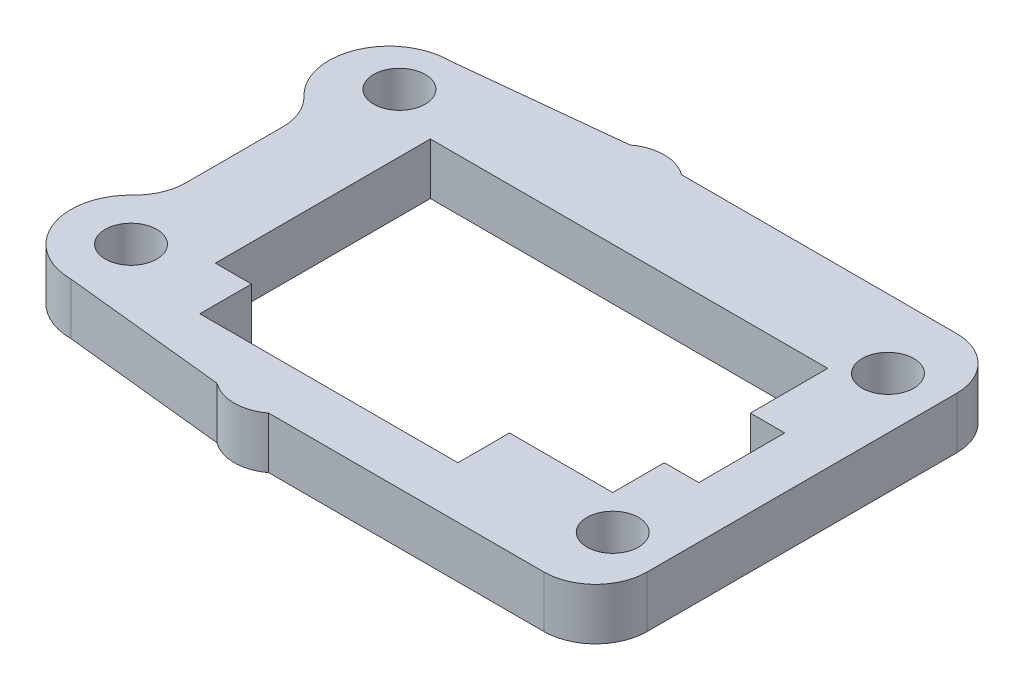
SolidWorks part; units mm, degrees
ref_plane "Alzado" through (0, 0, 0) normal (0, 0, 1) x (1, 0, 0)
ref_plane "Planta" through (0, 0, 0) normal (0, 1, 0) x (1, 0, 0)
ref_plane "Vista lateral" through (0, 0, 0) normal (1, 0, 0) x (0, 0, -1)
sketch "Croquis1" plane through (0, 0, 0) normal (0, 0, 1) x (1, 0, 0)
  line L0 (41558.3613, 58239.9576) -> (41574.3613, 58239.9576)
  line L1 (41544.3613, 58230.7672) -> (41544.3613, 58225.148)
  line L2 (41545.8613, 58216.9576) -> (41555.3613, 58215.9576)
  line L3 (41558.3613, 58215.9576) -> (41574.3613, 58215.9576)
  line L4 (41577.3613, 58218.9576) -> (41577.3613, 58236.9576)
  line L5 (41555.3613, 58239.9576) -> (41545.8613, 58238.9576)
  line L6 (41551.3613, 58236.9576) -> (41566.3613, 58236.9576)
  line L7 (41566.3613, 58236.9576) -> (41566.3613, 58233.9576)
  line L8 (41566.3613, 58233.9576) -> (41572.3613, 58233.9576)
  line L9 (41572.3613, 58233.9576) -> (41572.3613, 58230.9576)
  line L10 (41572.3613, 58230.9576) -> (41574.3613, 58230.9576)
  line L11 (41574.3613, 58230.9576) -> (41574.3613, 58225.9576)
  line L12 (41574.3613, 58225.9576) -> (41572.3613, 58225.9576)
  line L13 (41572.3613, 58225.9576) -> (41572.3613, 58221.4576)
  line L14 (41572.3613, 58221.4576) -> (41549.2613, 58221.4576)
  line L15 (41549.2613, 58221.4576) -> (41549.2613, 58233.9576)
  line L16 (41549.2613, 58233.9576) -> (41551.3613, 58233.9576)
  line L17 (41551.3613, 58233.9576) -> (41551.3613, 58236.9576)
  circle A0 centre (41545.8613, 58235.4576) radius 1.5
  arc A1 (41545.8613, 58238.9576) -> (41543.4382, 58232.932) centre (41545.8613, 58235.4576) ccw
  circle A4 centre (41545.8613, 58219.8576) radius 1.5
  arc A5 (41543.4382, 58222.9832) -> (41545.8613, 58216.9576) centre (41545.8613, 58220.4576) ccw
  arc A6 (41555.3613, 58215.9576) -> (41558.3613, 58215.9576) centre (41556.8613, 58217.9576) ccw
  circle A7 centre (41574.3613, 58219.9576) radius 1.5
  circle A8 centre (41574.3613, 58235.9576) radius 1.5
  arc A9 (41577.3613, 58236.9576) -> (41574.3613, 58239.9576) centre (41574.3613, 58236.9576) ccw
  arc A10 (41558.3613, 58239.9576) -> (41555.3613, 58239.9576) centre (41556.8613, 58237.9576) ccw
  arc A11 (41574.3613, 58215.9576) -> (41577.3613, 58218.9576) centre (41574.3613, 58218.9576) ccw
  arc A12 (41544.3613, 58230.7672) -> (41543.4382, 58232.932) centre (41541.3613, 58230.7672) ccw
  arc A13 (41543.4382, 58222.9832) -> (41544.3613, 58225.148) centre (41541.3613, 58225.148) ccw
extrude "Saliente-Extruir1" add sketch "Croquis1" along normal blind 3
move or copy body "Sólido-Mover/Copiar1" bodies to move or copy 101 copy no rotation origin (0, 58227.9576, 1.5) rotation axis (1, 0, 0) rotation angle 90
